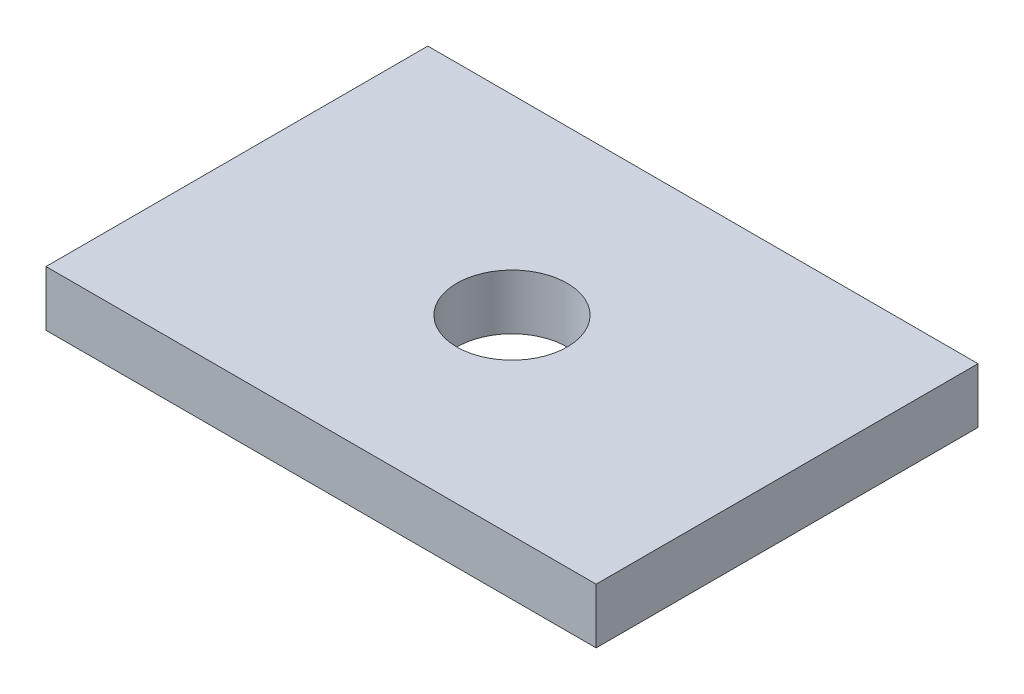
SolidWorks part; units mm, degrees
ref_plane "Front Plane" through (0, 0, 0) normal (0, 0, 1) x (1, 0, 0)
ref_plane "Top Plane" through (0, 0, 0) normal (0, 1, 0) x (1, 0, 0)
ref_plane "Right Plane" through (0, 0, 0) normal (1, 0, 0) x (0, 0, -1)
sketch "Sketch1" plane through (0, 0, 0) normal (0, 1, 0) x (1, 0, 0)
  line L1 (-63.2459, -43.9001) -> (63.2459, -43.9001)
  line L2 (-63.2459, -43.9001) -> (-63.2459, 43.9001)
  line L3 (-63.2459, 43.9001) -> (63.2459, 43.9001)
  line L4 (63.2459, -43.9001) -> (63.2459, 43.9001)
  line L5 (-63.2459, -43.9001) -> (63.2459, 43.9001) construction
  line L6 (-63.2459, 43.9001) -> (63.2459, -43.9001) construction
  point P0 (0, 0)
extrude "Boss-Extrude1" add sketch "Sketch1" along normal blind 12.7
hole_wizard "1 (1) Diameter Hole1" positions "Sketch2" profile "Sketch3" hole size "1" standard "ANSI Inch" end condition through all
sketch "Sketch2" plane through (0, 12.7, 0) normal (0, 1, 0) x (1, 0, 0)
  point P0 (0, 0)
sketch "Sketch3" plane through (0, 12.7, 0) normal (1, 0, 0) x (0, 0, 1)
  line L0 (0, 0) -> (0, 12.7)
  line L1 (0, 12.7) -> (12.7, 12.7)
  line L2 (12.7, 12.7) -> (12.7, 0)
  line L5 (12.7, 0) -> (0, 0)
  line L11 (0, -6.35) -> (0, 107.95) construction
  dimension "Thru Hole Dia." = 25.4
  dimension "Thru Hole Depth" = 12.7
